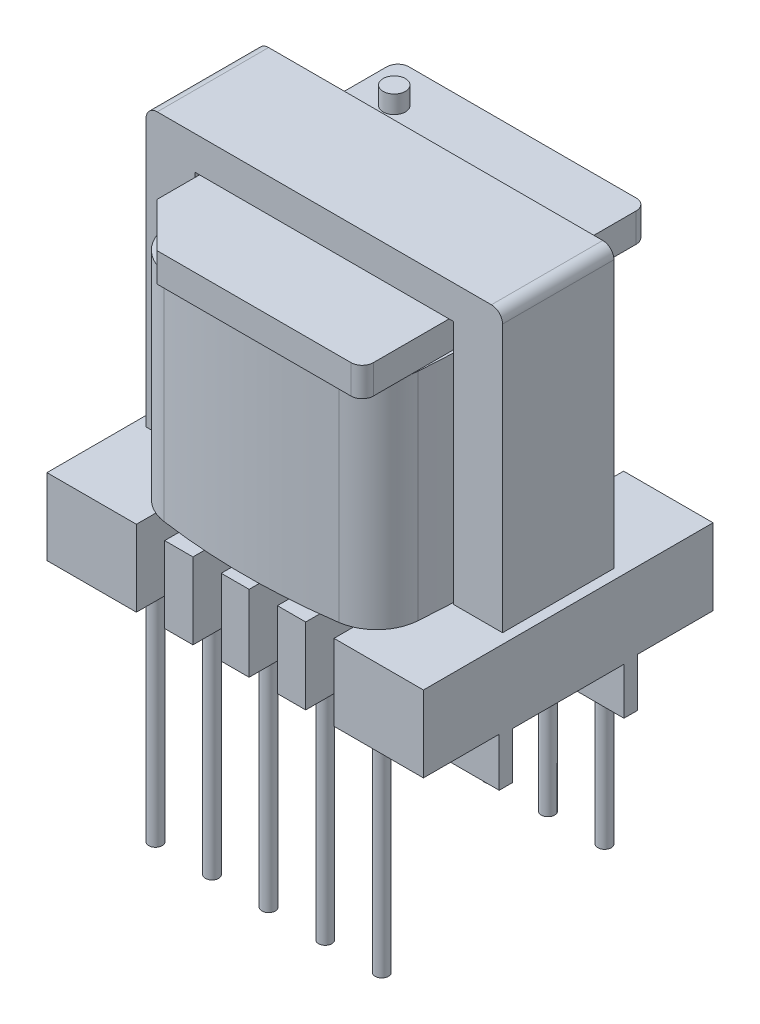
SolidWorks part; units mm, degrees
ref_plane "Спереди" through (0, 0, 0) normal (0, 0, 1) x (1, 0, 0)
ref_plane "Сверху" through (0, 0, 0) normal (0, 1, 0) x (1, 0, 0)
ref_plane "Справа" through (0, 0, 0) normal (1, 0, 0) x (0, 0, -1)
sketch "Эскиз2" plane through (0, 0, 0) normal (0, 1, 0) x (1, 0, 0)
  line L1 (-8, -2.5) -> (8, -2.5)
  line L2 (-8, -2.5) -> (-8, 2.5)
  line L3 (-8, 2.5) -> (8, 2.5)
  line L4 (8, -2.5) -> (8, 2.5)
  line L5 (-8, -2.5) -> (8, 2.5) construction
  line L6 (-8, 2.5) -> (8, -2.5) construction
  point P0 (0, 0)
  dimension "D1" = 16
  dimension "D2" = 5
extrude "Вытянуть1" add sketch "Эскиз2" along normal blind 14.5
sketch "Эскиз3" plane through (0, 0, 2.5) normal (0, 0, 1) x (1, 0, 0)
  line L0 (-8, 14.5) -> (-8, 0) construction
  line L1 (5.8, 13) -> (-5.8, 13)
  line L2 (5.8, 13) -> (5.8, 1.5)
  line L3 (5.8, 1.5) -> (-5.8, 1.5)
  line L4 (-5.8, 13) -> (-5.8, 1.5)
  line L5 (-8, 14.5) -> (8, 14.5) construction
  line L6 (-8, 0) -> (8, 0) construction
  line L7 (8, 14.5) -> (8, 0) construction
  dimension "D1" = 2.2
  dimension "D2" = 1.5
  dimension "D3" = 1.5
  dimension "D4" = 2.2
extrude "Вытянуть2" cut sketch "Эскиз3" against normal through all
sketch "Эскиз4" plane through (0, 13, 0) normal (0, -1, 0) x (1, 0, 0)
  line L1 (-5.1, -6.4) -> (5.1, -6.4)
  line L2 (-5.6, -5.9) -> (-5.6, 6.4)
  line L3 (-5.6, 6.4) -> (5.1, 6.4)
  line L4 (5.6, -5.9) -> (5.6, 5.9)
  line L5 (-5.6, -6.4) -> (5.6, 6.4) construction
  line L6 (-5.6, 6.4) -> (5.6, -6.4) construction
  arc A0 (5.1, 6.4) -> (5.6, 5.9) centre (5.1, 5.9) cw
  arc A2 (-5.1, -6.4) -> (-5.6, -5.9) centre (-5.1, -5.9) cw
  arc A3 (5.1, -6.4) -> (5.6, -5.9) centre (5.1, -5.9) ccw
  point P0 (0, 0)
  point P11 (0, 0)
  dimension "D3" = 0.5
  dimension "D4" = 0.5
  dimension "D1" = 11.2
  dimension "D2" = 12.8
extrude "Вытянуть3" add sketch "Эскиз4" along normal blind 1.3
sketch "Эскиз6" plane through (0, 1.5, 0) normal (0, 1, 0) x (-1, 0, 0)
  line L1 (8.45, -6.5) -> (-8.45, -6.5)
  line L2 (8.45, -6.5) -> (8.45, 6.5)
  line L3 (8.45, 6.5) -> (-8.45, 6.5)
  line L4 (-8.45, -6.5) -> (-8.45, 6.5)
  line L5 (8.45, -6.5) -> (-8.45, 6.5) construction
  line L6 (8.45, 6.5) -> (-8.45, -6.5) construction
  point P0 (0, 0)
  dimension "D1" = 16.9
  dimension "D2" = 13
extrude "Вытянуть7" add sketch "Эскиз6" along normal blind 0.5 and the other way blind 5.1
sketch "Croquis1" plane through (-8.45, 0, 0) normal (-1, 0, 0) x (0, 0, 1)
  line L0 (2.5, 14.5) -> (2.5, 2) construction
  line L1 (-2.5, -1.5) -> (2.5, -1.5)
  line L2 (-2.5, -1.5) -> (-2.5, -4.119)
  line L3 (-2.5, -4.119) -> (2.5, -4.119)
  line L4 (2.5, -1.5) -> (2.5, -4.119)
  line L5 (3.1, -1.4194) -> (7.2804, -1.4194)
  line L6 (3.1, -1.4194) -> (3.1, -4.119)
  line L7 (3.1, -4.119) -> (7.2804, -4.119)
  line L8 (7.2804, -1.4194) -> (7.2804, -4.119)
  line L9 (-3.1, -1.4194) -> (-8.071, -1.4194)
  line L10 (-3.1, -1.4194) -> (-3.1, -4.119)
  line L11 (-3.1, -4.119) -> (-8.071, -4.119)
  line L12 (-8.071, -1.4194) -> (-8.071, -4.119)
  line L13 (-2.5, 14.5) -> (-2.5, 2) construction
  line L15 (-6.5, -3.6) -> (6.5, -3.6) construction
  dimension "D1" = 0.6
  dimension "D2" = 0.6
  dimension "D3" = 2.1
extrude "Cortar-Extruir1" cut sketch "Croquis1" against normal up to next
sketch "Эскиз11" plane through (0, 13, 0) normal (0, 1, 0) x (-1, 0, 0)
  line L2 (5.6, 4.4) -> (3.6, 6.4)
  line L4 (-5.1, 6.4) -> (5.6, 6.4) construction
  line L16 (5.6, 4.4) -> (5.6, 6.4)
  line L18 (5.6, 6.4) -> (3.6, 6.4)
  point P0 (5.6, 4.45)
  dimension "D1" = 2
extrude "Вытянуть10" cut sketch "Эскиз11" against normal up to next
sketch "Эскиз18" plane through (0, 2, 0) normal (0, 1, 0) x (-1, 0, 0)
  line L0 (0, 5.5) -> (0, 8.5) construction
  line L1 (5.5, -5.5) -> (-5.5, -5.5) construction
  line L2 (5.5, -5.5) -> (5.5, 5.5) construction
  line L3 (5.5, 5.5) -> (-5.5, 5.5) construction
  line L4 (-5.5, -5.5) -> (-5.5, 5.5) construction
  line L5 (5.5, -5.5) -> (-5.5, 5.5) construction
  line L6 (5.5, 5.5) -> (-5.5, -5.5) construction
  line L7 (0, -5.5) -> (0, -8.5) construction
  line L8 (-5.5, 0) -> (-6, 0) construction
  line L10 (5.5, 0) -> (8, 0) construction
  arc A0 (5.5, -5.5) -> (-5.5, -5.5) centre (0, 21.6169) cw
  arc A1 (5.5, -5.5) -> (5.5, 5.5) centre (-48, 0) ccw
  arc A2 (-5.5, -5.5) -> (-5.5, 5.5) centre (48, 0) cw
  arc A3 (5.5, 5.5) -> (-5.5, 5.5) centre (0, -21.6169) ccw
  point P0 (0, 0)
  dimension "D1" = 11
  dimension "D2" = 11
extrude "Вытянуть19" add sketch "Эскиз18" along normal up to vertex (9.7 mm away) separate body
fillet "Скругление1" radius 2 4 edges at (-5.5, 6.85, -5.5) (5.5, 6.85, -5.5) (5.5, 6.85, 5.5) (-5.5, 6.85, 5.5)
fillet "Redondeo1" radius 0.5 2 edges at (-8, 14.5, 0) (8, 14.5, 0)
sketch "Эскиз19" plane through (0, 13, 0) normal (0, 1, 0) x (-1, 0, 0)
  circle A0 centre (3.9242, -4.5645) radius 0.5
  dimension "D1" = 1
extrude "Вытянуть20" add sketch "Эскиз19" along normal blind 0.8
sketch "Croquis2" plane through (0, -1.4194, 0) normal (0, -1, 0) x (1, 0, 0)
  line L0 (0, 7.2445) -> (0, -7.9256) construction
  line L1 (1.895, -3.4804) -> (0.625, -3.4804)
  line L2 (-1.895, -6.9804) -> (-0.625, -6.9804)
  line L3 (-1.895, -6.9804) -> (-1.895, -3.4804)
  line L4 (-1.895, -3.4804) -> (-0.625, -3.4804)
  line L5 (-0.625, -6.9804) -> (-0.625, -3.4804)
  line L6 (-3.165, -6.9804) -> (-4.435, -6.9804)
  line L7 (-3.165, -6.9804) -> (-3.165, -3.4804)
  line L8 (-3.165, -3.4804) -> (-4.435, -3.4804)
  line L9 (-4.435, -6.9804) -> (-4.435, -3.4804)
  line L10 (0.625, -6.9804) -> (0.625, -3.4804)
  line L11 (1.895, -6.9804) -> (0.625, -6.9804)
  line L12 (1.895, -6.9804) -> (1.895, -3.4804)
  line L13 (3.165, -3.4804) -> (4.435, -3.4804)
  line L14 (4.435, -6.9804) -> (4.435, -3.4804)
  line L15 (3.165, -6.9804) -> (4.435, -6.9804)
  line L16 (3.165, -6.9804) -> (3.165, -3.4804)
  line L17 (-10.2243, 0) -> (9.7739, 0) construction
  line L18 (3.165, 6.9804) -> (3.165, 3.4804)
  line L19 (3.165, 6.9804) -> (4.435, 6.9804)
  line L20 (4.435, 6.9804) -> (4.435, 3.4804)
  line L21 (3.165, 3.4804) -> (4.435, 3.4804)
  line L22 (1.895, 6.9804) -> (1.895, 3.4804)
  line L23 (1.895, 6.9804) -> (0.625, 6.9804)
  line L24 (0.625, 6.9804) -> (0.625, 3.4804)
  line L25 (1.895, 3.4804) -> (0.625, 3.4804)
  line L26 (-1.895, 3.4804) -> (-0.625, 3.4804)
  line L27 (-0.625, 6.9804) -> (-0.625, 3.4804)
  line L28 (-1.895, 6.9804) -> (-0.625, 6.9804)
  line L29 (-1.895, 6.9804) -> (-1.895, 3.4804)
  line L30 (-3.165, 3.4804) -> (-4.435, 3.4804)
  line L31 (-4.435, 6.9804) -> (-4.435, 3.4804)
  line L32 (-3.165, 6.9804) -> (-4.435, 6.9804)
  line L33 (-3.165, 6.9804) -> (-3.165, 3.4804)
  dimension "D1" = 3.5
  dimension "D2" = 1.27
  dimension "D3" = 0.625
  dimension "D4" = 1.27
extrude "Cortar-Extruir2" cut sketch "Croquis2" against normal up to next (3.4194 mm away)
sketch "Croquis3" plane through (0, -1.4194, 0) normal (0, -1, 0) x (1, 0, 0)
  line L0 (2.53, 6.5) -> (2.53, 2.5) construction
  line L1 (1.895, 6.5) -> (3.165, 6.5) construction
  line L2 (8.45, 2.5) -> (-8.45, 2.5) construction
  line L3 (-10.8864, 0) -> (9.6343, 0) construction
  circle A0 centre (0, 5) radius 0.3
  circle A1 centre (2.54, 5) radius 0.3
  circle A2 centre (5.08, 5) radius 0.3
  circle A3 centre (-2.54, 5) radius 0.3
  circle A4 centre (-5.08, 5) radius 0.3
  circle A5 centre (5.08, -5) radius 0.3
  circle A6 centre (2.54, -5) radius 0.3
  circle A7 centre (0, -5) radius 0.3
  circle A8 centre (-2.54, -5) radius 0.3
  dimension "D3" = 0.6
  dimension "D6" = 2.54
  dimension "D1" = 5
  dimension "D2" = 2.54
  dimension "D4" = 2.54
  dimension "D5" = 2.54
extrude "Saliente-Extruir1" add sketch "Croquis3" along normal blind 10
